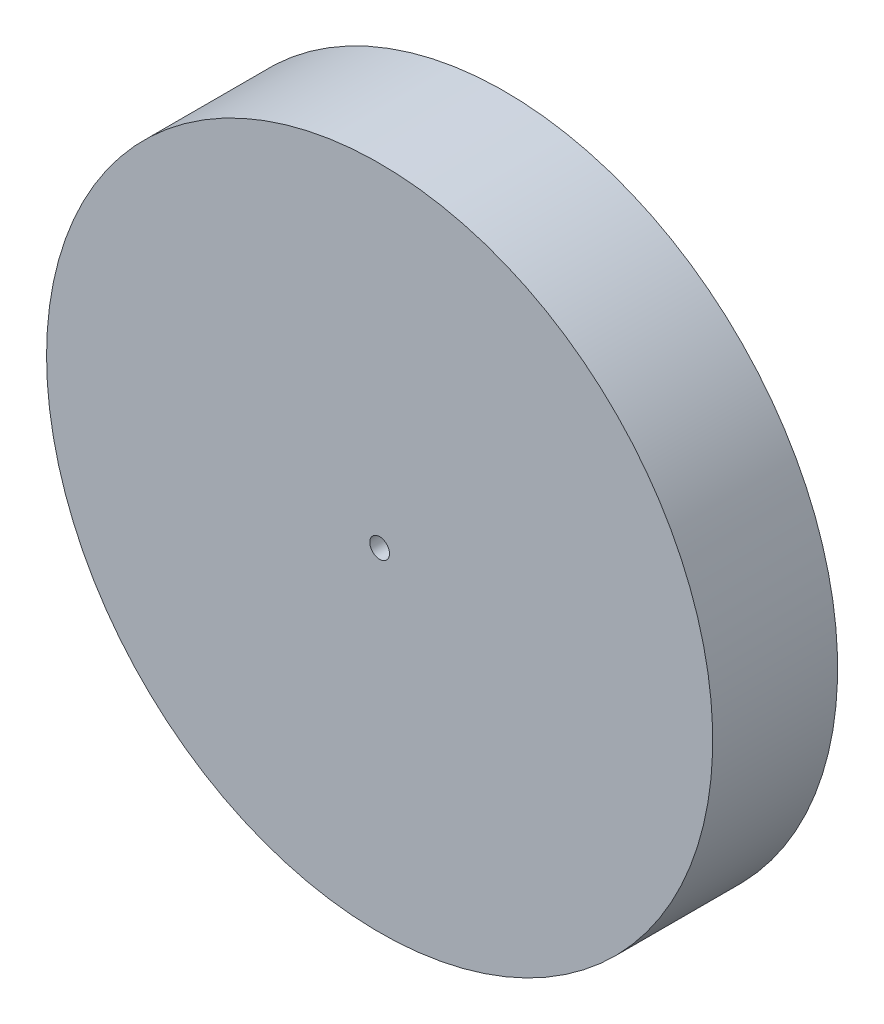
SolidWorks part; units mm, degrees
material "BUTYL"
ref_plane "Front Plane" through (0, 0, 0) normal (0, 0, 1) x (1, 0, 0)
ref_plane "Top Plane" through (0, 0, 0) normal (0, 1, 0) x (1, 0, 0)
ref_plane "Right Plane" through (0, 0, 0) normal (1, 0, 0) x (0, 0, -1)
sketch "Sketch1" plane through (0, 0, 0) normal (0, 0, 1) x (1, 0, 0)
  circle A0 centre (0, 0) radius 50.8
  dimension "D1" = 101.6
extrude "Boss-Extrude1" add sketch "Sketch1" along normal blind 19.05
hole_wizard "Ø3.0mm Clearance Dowel Hole1" positions "Sketch2" profile "Sketch3" hole size "Ø3.0" standard "ANSI Metric" end condition through all
sketch "Sketch2" plane through (0, 0, 19.05) normal (0, 0, 1) x (1, 0, 0)
  point P0 (0, 0)
sketch "Sketch3" plane through (0, 0, 19.05) normal (1, 0, 0) x (0, -1, 0)
  line L0 (0, 0) -> (0, 19.05)
  line L1 (0, 19.05) -> (1.5, 19.05)
  line L2 (1.5, 19.05) -> (1.5, 0)
  line L5 (1.5, 0) -> (0, 0)
  line L11 (0, -6.35) -> (0, 107.95) construction
  dimension "Thru Hole Dia." = 3
  dimension "Thru Hole Depth" = 19.05
